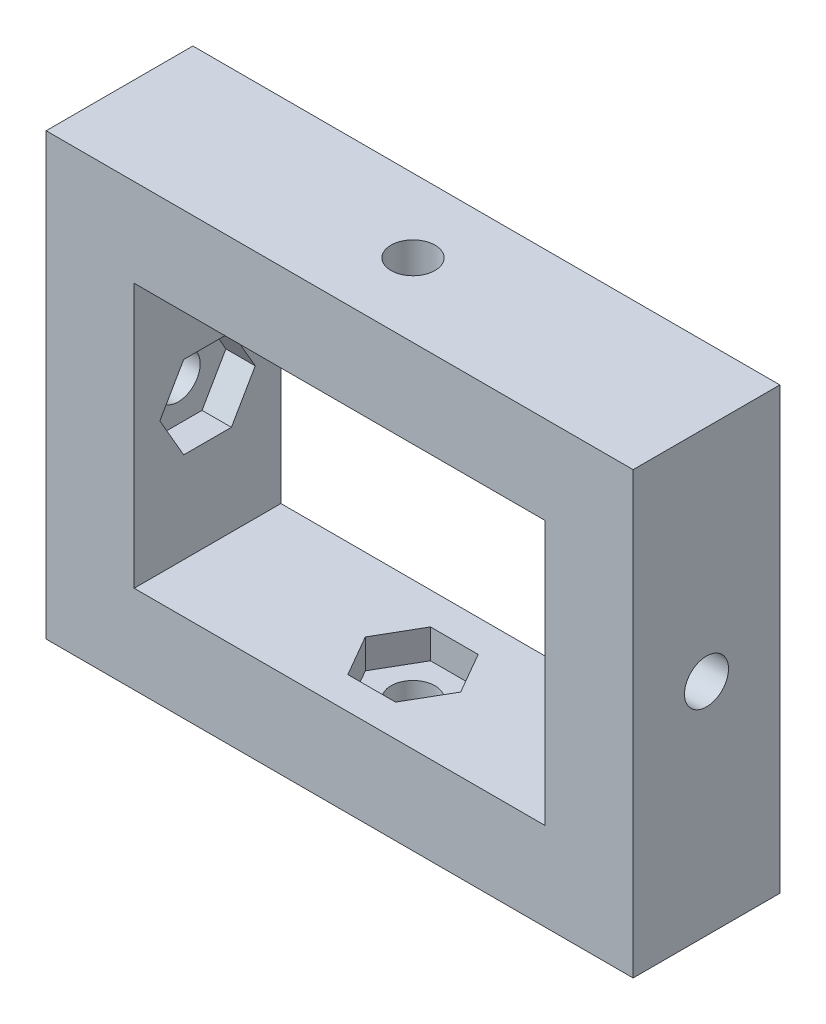
SolidWorks part; units mm, degrees
material "ABS"
ref_plane "Front Plane" through (0, 0, 0) normal (0, 0, 1) x (1, 0, 0)
ref_plane "Top Plane" through (0, 0, 0) normal (0, 1, 0) x (1, 0, 0)
ref_plane "Right Plane" through (0, 0, 0) normal (1, 0, 0) x (0, 0, -1)
ref_plane "Plane1" through (0, 0, 0) normal (0, 0, -1) x (-1, 0, 0)
sketch "Sketch1" plane through (0, 0, 0) normal (0, 0, -1) x (-1, 0, 0)
  line L0 (6, 24) -> (-34, 24)
  line L1 (-34, 24) -> (-34, -6)
  line L2 (-34, -6) -> (6, -6)
  line L3 (6, -6) -> (6, 24)
extrude "Boss-Extrude1" add sketch "Sketch1" against normal blind 10
sketch "Sketch2" plane through (0, 0, 10) normal (0, 0, 1) x (1, 0, 0)
  line L0 (28, 18) -> (0, 18)
  line L1 (0, 18) -> (0, 0)
  line L2 (0, 0) -> (28, 0)
  line L3 (28, 0) -> (28, 18)
extrude "Cut-Extrude1" cut sketch "Sketch2" against normal through all
sketch "Sketch3" plane through (0, 0, 0) normal (1, 0, 0) x (0, 0, -1)
  line L0 (-8.25, 9) -> (-6.625, 6.1854)
  line L1 (-6.625, 6.1854) -> (-3.375, 6.1854)
  line L2 (-3.375, 6.1854) -> (-1.75, 9)
  line L3 (-1.75, 9) -> (-3.375, 11.8146)
  line L4 (-3.375, 11.8146) -> (-6.625, 11.8146)
  line L5 (-6.625, 11.8146) -> (-8.25, 9)
extrude "Cut-Extrude2" cut sketch "Sketch3" against normal blind 2
sketch "Sketch4" plane through (0, 18, 0) normal (0, -1, 0) x (1, 0, 0)
  line L0 (17.25, 5) -> (15.625, 7.8146)
  line L1 (15.625, 7.8146) -> (12.375, 7.8146)
  line L2 (12.375, 7.8146) -> (10.75, 5)
  line L3 (10.75, 5) -> (12.375, 2.1854)
  line L4 (12.375, 2.1854) -> (15.625, 2.1854)
  line L5 (15.625, 2.1854) -> (17.25, 5)
extrude "Cut-Extrude3" cut sketch "Sketch4" against normal blind 2
sketch "Sketch5" plane through (28, 0, 0) normal (-1, 0, 0) x (0, 0, 1)
  line L0 (1.75, 9) -> (3.375, 6.1854)
  line L1 (3.375, 6.1854) -> (6.625, 6.1854)
  line L2 (6.625, 6.1854) -> (8.25, 9)
  line L3 (8.25, 9) -> (6.625, 11.8146)
  line L4 (6.625, 11.8146) -> (3.375, 11.8146)
  line L5 (3.375, 11.8146) -> (1.75, 9)
extrude "Cut-Extrude4" cut sketch "Sketch5" against normal blind 2
sketch "Sketch6" plane through (0, 0, 0) normal (0, 1, 0) x (-1, 0, 0)
  line L0 (-17.25, 5) -> (-15.625, 2.1854)
  line L1 (-15.625, 2.1854) -> (-12.375, 2.1854)
  line L2 (-12.375, 2.1854) -> (-10.75, 5)
  line L3 (-10.75, 5) -> (-12.375, 7.8146)
  line L4 (-12.375, 7.8146) -> (-15.625, 7.8146)
  line L5 (-15.625, 7.8146) -> (-17.25, 5)
extrude "Cut-Extrude5" cut sketch "Sketch6" against normal blind 2
hole_wizard "Ø3.0 (3) Diameter Hole1" positions "Sketch8" profile "Sketch7" hole size "Ø3.0" standard "ANSI Metric"
sketch "Sketch8" plane through (-2, 0, 0) normal (1, 0, 0) x (0, 0, -1)
  point P0 (-5, 9)
sketch "Sketch7" plane through (-2, 9, 5) normal (0, 1, 0) x (0, 0, -1)
  line L0 (0, 0) -> (0, 4)
  line L1 (0, 4) -> (1.5, 4)
  line L2 (1.5, 4) -> (1.5, 0)
  line L5 (1.5, 0) -> (0, 0)
  line L11 (0, -6.35) -> (0, 107.95) construction
  dimension "Thru Hole Dia." = 3
  dimension "Thru Hole Depth" = 4
hole_wizard "Ø3.0 (3) Diameter Hole2" positions "Sketch10" profile "Sketch9" hole size "Ø3.0" standard "ANSI Metric"
sketch "Sketch10" plane through (0, 20, 0) normal (0, -1, 0) x (-1, 0, 0)
  point P0 (-14, -5)
sketch "Sketch9" plane through (14, 20, 5) normal (1, 0, 0) x (0, 0, -1)
  line L0 (0, 0) -> (0, 4)
  line L1 (0, 4) -> (1.5, 4)
  line L2 (1.5, 4) -> (1.5, 0)
  line L5 (1.5, 0) -> (0, 0)
  line L11 (0, -6.35) -> (0, 107.95) construction
  dimension "Thru Hole Dia." = 3
  dimension "Thru Hole Depth" = 4
hole_wizard "Ø3.0 (3) Diameter Hole3" positions "Sketch12" profile "Sketch11" hole size "Ø3.0" standard "ANSI Metric"
sketch "Sketch12" plane through (30, 0, 0) normal (-1, 0, 0) x (0, 0, 1)
  point P0 (5, 9)
sketch "Sketch11" plane through (30, 9, 5) normal (0, 1, 0) x (0, 0, 1)
  line L0 (0, 0) -> (0, 4)
  line L1 (0, 4) -> (1.5, 4)
  line L2 (1.5, 4) -> (1.5, 0)
  line L5 (1.5, 0) -> (0, 0)
  line L11 (0, -6.35) -> (0, 107.95) construction
  dimension "Thru Hole Dia." = 3
  dimension "Thru Hole Depth" = 4
hole_wizard "Ø3.0 (3) Diameter Hole4" positions "Sketch14" profile "Sketch13" hole size "Ø3.0" standard "ANSI Metric"
sketch "Sketch14" plane through (0, -2, 0) normal (0, 1, 0) x (1, 0, 0)
  point P0 (14, -5)
sketch "Sketch13" plane through (14, -2, 5) normal (1, 0, 0) x (0, 0, 1)
  line L0 (0, 0) -> (0, 4)
  line L1 (0, 4) -> (1.5, 4)
  line L2 (1.5, 4) -> (1.5, 0)
  line L5 (1.5, 0) -> (0, 0)
  line L11 (0, -6.35) -> (0, 107.95) construction
  dimension "Thru Hole Dia." = 3
  dimension "Thru Hole Depth" = 4
